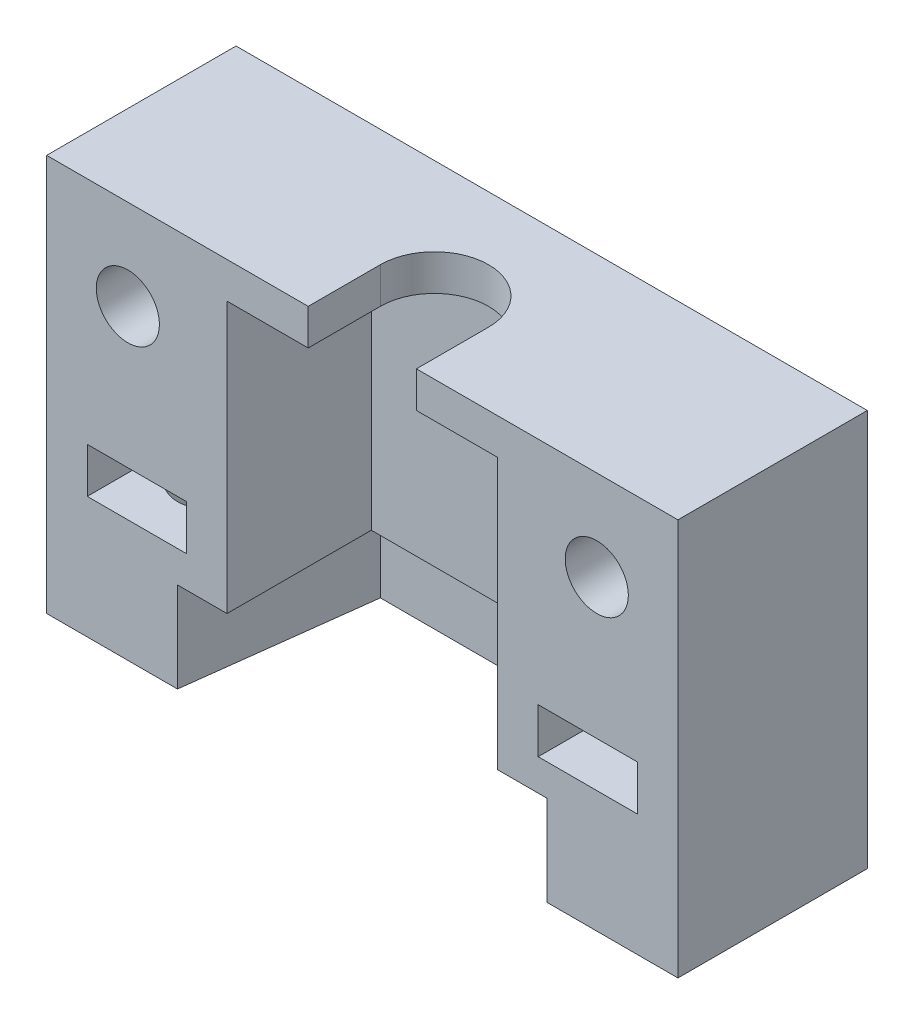
SolidWorks part; units mm, degrees
ref_plane "Plan de face" through (0, 0, 0) normal (0, 0, 1) x (1, 0, 0)
ref_plane "Plan de dessus" through (0, 0, 0) normal (0, 1, 0) x (1, 0, 0)
ref_plane "Plan de droite" through (0, 0, 0) normal (1, 0, 0) x (0, 0, -1)
sketch "Esquisse1" plane through (0, 0, 0) normal (0, 1, 0) x (1, 0, 0)
  line L0 (-17.5, 0) -> (17.5, 0) construction
  line L1 (-17.5, 6.5) -> (17.5, 6.5)
  line L2 (-17.5, 6.5) -> (-17.5, -6.5)
  line L3 (-17.5, -6.5) -> (17.5, -6.5)
  line L4 (17.5, 6.5) -> (17.5, -6.5)
  line L5 (-17.5, 6.5) -> (17.5, -6.5) construction
  line L6 (-17.5, -6.5) -> (17.5, 6.5) construction
  line L7 (-10.5, -6) -> (10.5, -6)
  line L8 (10.5, -6) -> (9, 6)
  line L9 (9, 6) -> (-9, 6)
  line L10 (-9, 6) -> (-10.5, -6)
  line L11 (0, 6) -> (0, -6) construction
  circle A0 centre (-12.5, 0) radius 1.75
  circle A1 centre (12.5, 0) radius 1.5
  point P0 (0, 0)
  point P18 (0, 0)
  dimension "D5" = 3
  dimension "D6" = 3.5
  dimension "D1" = 35
  dimension "D2" = 13
  dimension "D3" = 25
  dimension "D4" = 12.5
  dimension "D7" = 21
  dimension "D8" = 18
  dimension "D9" = 12
extrude "Boss.-Extru.1" add sketch "Esquisse1" along normal blind 5
sketch "Esquisse2" plane through (0, 5, 0) normal (0, 1, 0) x (1, 0, 0)
  line L1 (-7.5, 4) -> (7.5, 4)
  line L2 (-7.5, 4) -> (-7.5, -4)
  line L3 (-7.5, -4) -> (7.5, -4)
  line L4 (17.5, -6.5) -> (17.5, 6.5)
  line L5 (17.5, 6.5) -> (-17.5, 6.5)
  line L6 (-17.5, 6.5) -> (-17.5, -6.5)
  line L7 (-17.5, -6.5) -> (17.5, -6.5)
  line L8 (17.5, -6.5) -> (17.5, 6.5)
  line L9 (17.5, 6.5) -> (-17.5, 6.5)
  line L10 (-17.5, 6.5) -> (-17.5, -6.5)
  line L11 (-17.5, -6.5) -> (17.5, -6.5)
  line L12 (7.5, 4) -> (7.5, -4)
  line L13 (-7.5, 4) -> (7.5, -4) construction
  line L14 (-7.5, -4) -> (7.5, 4) construction
  circle A0 centre (12.5, 0) radius 1.5 construction
  circle A1 centre (-12.5, 0) radius 1.75 construction
  circle A2 centre (12.5, 0) radius 1.5
  circle A3 centre (-12.5, 0) radius 1.75
  point P10 (0, 0)
  dimension "D2" = 8
  dimension "D3" = 15
  dimension "D1" = 0
extrude "Boss.-Extru.2" add sketch "Esquisse2" along normal blind 15
sketch "Esquisse3" plane through (0, 20, 0) normal (0, 1, 0) x (1, 0, 0)
  line L1 (-17.5, -6.5) -> (17.5, -6.5)
  line L2 (-17.5, -6.5) -> (-17.5, 6.5)
  line L3 (-17.5, 6.5) -> (17.5, 6.5)
  line L4 (17.5, -6.5) -> (17.5, 6.5)
  line L5 (-17.5, -6.5) -> (17.5, 6.5) construction
  line L6 (-17.5, 6.5) -> (17.5, -6.5) construction
  circle A0 centre (0, 0) radius 3
  dimension "D1" = 6
extrude "Boss.-Extru.3" add sketch "Esquisse3" along normal blind 2
ref_plane "Plan1" through (0, 0, 4) normal (0, 0, -1) x (-1, 0, 0)
sketch "Esquisse9" plane through (0, 0, 6.5) normal (0, 0, 1) x (1, 0, 0)
  line L0 (-17.5, 17) -> (17.5, 17) construction
  line L1 (-17.5, 22) -> (-17.5, 0) construction
  line L2 (17.5, 22) -> (17.5, 0) construction
  line L3 (-17.5, 22) -> (17.5, 22) construction
  circle A0 centre (-13, 17) radius 1.75
  circle A1 centre (13, 17) radius 1.75
  dimension "D1" = 3.5
  dimension "D2" = 3.5
  dimension "D3" = 4.5
  dimension "D4" = 4.5
  dimension "D5" = 5
extrude "Enlèv. mat.-Extru.5" cut sketch "Esquisse9" against normal through all
sketch "Esquisse5" plane through (0, 0, 4) normal (0, 0, -1) x (-1, 0, 0)
  line L1 (-23.1916, -5.7851) -> (29.5437, -5.7851)
  line L2 (-23.1916, -5.7851) -> (-23.1916, 26.2888)
  line L3 (-23.1916, 26.2888) -> (29.5437, 26.2888)
  line L4 (29.5437, -5.7851) -> (29.5437, 26.2888)
extrude "Enlèv. mat.-Extru.1" cut sketch "Esquisse5" against normal through all
sketch "Esquisse4" plane through (0, 0, 4) normal (0, 0, -1) x (-1, 0, 0)
  line L0 (12.5, 0) -> (12.5, 22) construction
  line L1 (17.5, 0) -> (10.25, 0) construction
  line L2 (9.75, 6.75) -> (15.25, 6.75)
  line L3 (9.75, 6.75) -> (9.75, 9.25)
  line L4 (9.75, 9.25) -> (15.25, 9.25)
  line L5 (15.25, 6.75) -> (15.25, 9.25)
  line L6 (9.75, 6.75) -> (15.25, 9.25) construction
  line L7 (9.75, 9.25) -> (15.25, 6.75) construction
  line L8 (-17.5, 22) -> (17.5, 22) construction
  line L13 (17.5, 22) -> (17.5, 0) construction
  point P2 (12.5, 8)
  point P7 (12.6565, 0)
  point P10 (13.1215, 22)
  point P15 (12.3915, 0)
  dimension "D1" = 5.5
  dimension "D2" = 2.5
  dimension "D3" = 5
  dimension "D4" = 8
sketch "Esquisse6" plane through (0, 20, 0) normal (0, -1, 0) x (1, 0, 0)
  line L0 (-3, 0) -> (-3, 4)
  line L1 (-55, 4) -> (55, 4) construction
  line L2 (-3, 4) -> (3, 4)
  line L3 (3, 4) -> (3, 0)
  circle A0 centre (0, 0) radius 3 construction
  arc A1 (-3, 0) -> (3, 0) centre (0, 0) cw
  circle M3 centre (0, 0) radius 3
  line M6 (7.5, 4) -> (-7.5, 4)
extrude "Enlèv. mat.-Extru.2" cut sketch "Esquisse6" against normal through all contours L3 L0 M6 M3
extrude "Enlèv. mat.-Extru.3" cut sketch "Esquisse4" along normal blind 4
sketch "Esquisse7" plane through (0, 6.75, 0) normal (0, 1, 0) x (1, 0, 0)
  line L0 (-9.75, 0) -> (-9.75, -4) construction
  line L1 (-9.75, -1.5877) -> (-9.75, 1.5877)
  line L2 (-9.75, 1.5877) -> (-12.5, 3.1754)
  line L3 (-12.5, 3.1754) -> (-15.25, 1.5877)
  line L4 (-15.25, 1.5877) -> (-15.25, -1.5877)
  line L5 (-15.25, -1.5877) -> (-12.5, -3.1754)
  line L6 (-12.5, -3.1754) -> (-9.75, -1.5877)
  line L8 (-15.25, 0) -> (-15.25, -4) construction
  circle A0 centre (-12.5, 0) radius 2.75 construction
  point P0 (-12.5, 0)
  point P12 (-11.617, -3.4198)
  point P13 (-12.5, 0.4105)
  point P14 (0, 0)
extrude "Enlèv. mat.-Extru.4" cut sketch "Esquisse7" along normal blind 2.5
ref_plane "Plan2" through (0, 0, 0) normal (-1, 0, 0) x (0, 0, 1)
mirror "Symétrie1" about plane through (0, 0, 0) normal (-1, 0, 0) of "Enlèv. mat.-Extru.3", "Enlèv. mat.-Extru.4"
sketch "Esquisse10" plane through (0, 0, -6.5) normal (0, 0, -1) x (-1, 0, 0)
  line L1 (-10.25, 15.4123) -> (-10.25, 18.5877)
  line L2 (-10.25, 18.5877) -> (-13, 20.1754)
  line L3 (-13, 20.1754) -> (-15.75, 18.5877)
  line L4 (-15.75, 18.5877) -> (-15.75, 15.4123)
  line L5 (-15.75, 15.4123) -> (-13, 13.8246)
  line L6 (-13, 13.8246) -> (-10.25, 15.4123)
  line L7 (13, 13.8246) -> (15.75, 15.4123)
  line L8 (15.75, 15.4123) -> (15.75, 18.5877)
  line L9 (15.75, 18.5877) -> (13, 20.1754)
  line L10 (13, 20.1754) -> (10.25, 18.5877)
  line L11 (10.25, 18.5877) -> (10.25, 15.4123)
  line L12 (10.25, 15.4123) -> (13, 13.8246)
  circle A0 centre (-13, 17) radius 2.75 construction
  circle A1 centre (13, 17) radius 2.75 construction
  point P10 (-14.0511, 20.1754)
  dimension "D1" = 5.5
  dimension "D2" = 5.5
extrude "Enlèv. mat.-Extru.6" cut sketch "Esquisse10" against normal blind 2.5
